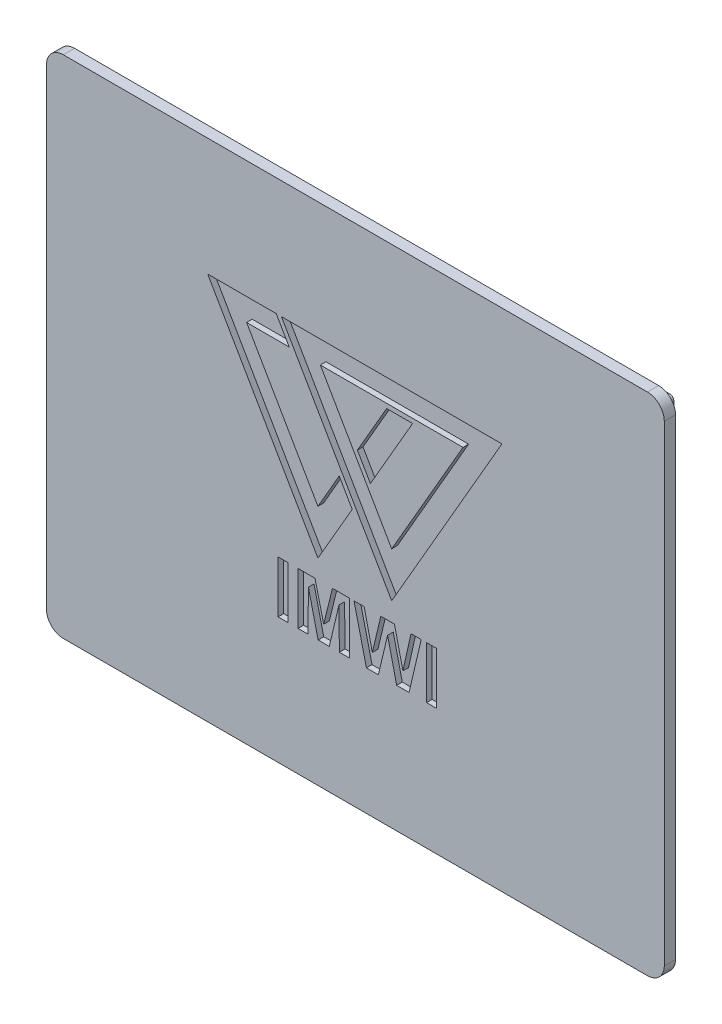
SolidWorks part; units mm, degrees
ref_plane "Front Plane" through (0, 0, 0) normal (0, 0, 1) x (1, 0, 0)
ref_plane "Top Plane" through (0, 0, 0) normal (0, 1, 0) x (1, 0, 0)
ref_plane "Right Plane" through (0, 0, 0) normal (1, 0, 0) x (0, 0, -1)
sketch "Sketch1" plane through (0, 0, 0) normal (0, 0, 1) x (1, 0, 0)
  line L0 (51.5, 41.5) -> (-51.5, 41.5)
  line L1 (-51.5, 41.5) -> (-51.5, -41.5)
  line L2 (-51.5, -41.5) -> (51.5, -41.5)
  line L3 (51.5, -41.5) -> (51.5, 41.5)
  line L4 (-52.7, 42) -> (-52.7, -42)
  line L5 (-52, -42.7) -> (52, -42.7)
  line L6 (52.7, -42) -> (52.7, 42)
  line L7 (52, 42.7) -> (-52, 42.7)
  arc A4 (-52.7, -42) -> (-52, -42.7) centre (-52, -42) ccw
  arc A5 (52, -42.7) -> (52.7, -42) centre (52, -42) ccw
  arc A6 (52.7, 42) -> (52, 42.7) centre (52, 42) ccw
  arc A7 (-52, 42.7) -> (-52.7, 42) centre (-52, 42) ccw
extrude "Boss-Extrude1" add sketch "Sketch1" along normal blind 2
sketch "Sketch3" plane through (0, 0, 2) normal (0, 0, 1) x (1, 0, 0)
  line L24 (52, 45) -> (-52, 45)
  line L25 (55, -42) -> (55, 42)
  line L26 (-52, -45) -> (52, -45)
  line L27 (-55, 42) -> (-55, -42)
  line L28 (52, 45) -> (-52, 45)
  line L29 (55, -42) -> (55, 42)
  line L30 (-52, -45) -> (52, -45)
  line L31 (-55, 42) -> (-55, -42)
  arc A20 (-52, 45) -> (-55, 42) centre (-52, 42) ccw
  arc A21 (55, 42) -> (52, 45) centre (52, 42) ccw
  arc A22 (52, -45) -> (55, -42) centre (52, -42) ccw
  arc A23 (-55, -42) -> (-52, -45) centre (-52, -42) ccw
  arc A24 (-52, 45) -> (-55, 42) centre (-52, 42) ccw
  arc A25 (55, 42) -> (52, 45) centre (52, 42) ccw
  arc A26 (52, -45) -> (55, -42) centre (52, -42) ccw
  arc A27 (-55, -42) -> (-52, -45) centre (-52, -42) ccw
  dimension "D1" = 2.3
extrude "Boss-Extrude3" add sketch "Sketch3" along normal blind 2
sketch "Sketch4" plane through (0, 0, 4) normal (0, 0, 1) x (1, 0, 0)
  line L3 (-13.1676, 24.0452) -> (26.0923, 24.0452)
  line L4 (26.0923, 24.0452) -> (6.4623, -9.9548)
  line L5 (6.4623, -9.9548) -> (-13.1676, 24.0452)
  line L6 (-6.6686, -9.9548) -> (-0.565, 0.6169)
  line L7 (-26.2985, 24.0452) -> (-6.6686, -9.9548)
  line L8 (12.9613, 24.0452) -> (-13.1676, 24.0452)
  line L9 (-19.3703, 20.0452) -> (-6.6686, -1.9548)
  line L10 (-6.6686, -1.9548) -> (-2.8744, 4.6169)
  line L11 (6.0331, 20.0452) -> (-6.2394, 20.0452)
  line L12 (19.1641, 20.0452) -> (6.4623, -1.9548)
  line L13 (6.4623, -1.9548) -> (-6.2394, 20.0452)
  line L14 (-6.2394, 20.0452) -> (19.1641, 20.0452)
  line L15 (-14.0913, 24.0452) -> (-11.7819, 20.0452)
  line L16 (-2.8744, 4.6169) -> (-0.565, 0.6169)
  line L17 (0.3588, 10.2169) -> (2.6682, 6.2169)
  line L18 (5.5712, 19.2452) -> (10.1901, 19.2452)
  line L19 (-11.7819, 20.0452) -> (-19.3703, 20.0452)
  line L20 (6.0331, 20.0452) -> (-19.3703, 20.0452) construction
  line L21 (-14.0913, 24.0452) -> (-26.2985, 24.0452)
  line L22 (12.9613, 24.0452) -> (-26.2985, 24.0452) construction
  line L24 (-6.6686, -1.9548) -> (6.0331, 20.0452) construction
  line L26 (-6.6686, -9.9548) -> (12.9613, 24.0452) construction
  line L27 (2.6682, 6.2169) -> (10.1901, 19.2452)
  line L28 (0.3588, 10.2169) -> (5.5712, 19.2452)
  point P0 (26.0923, 24.0452)
  dimension "D1" = 39.2598
  dimension "D2" = 10.425
  dimension "D4" = 0.8
  dimension "D5" = 0.8
  dimension "D6" = 0.8
  dimension "D7" = 0.8
  dimension "D8" = 15.0438
  dimension "D9" = 25.4034
  dimension "D10" = 39.2598
  dimension "D3" = 4
extrude "Cut-Extrude1" cut sketch "Sketch4" against normal blind 1 contours L5 L4 L3 L11 L14 L12 L13 | L28 L17 L27 L18 | L15 L21 L7 L6 L16 L10 L9 L19
sketch "Sketch5" plane through (0, 0, 4) normal (0, 0, 1) x (1, 0, 0)
  line L0 (-14.5911, -22.553) -> (16.5408, -22.553) construction
  text T0 "<b>IMWI</b>" font "Century Gothic" height in points 36
  point P2 (-29.727, -35.0494)
  point P3 (0, 0)
  point P5 (-33.3346, -34.8355)
  point P6 (-14.819, -29.6258)
  point P7 (-15.1262, -32.0963)
  point P8 (-14.5911, -22.553)
  dimension "D1" = 31.1319
extrude "Cut-Extrude2" cut sketch "Sketch5" against normal blind 1
